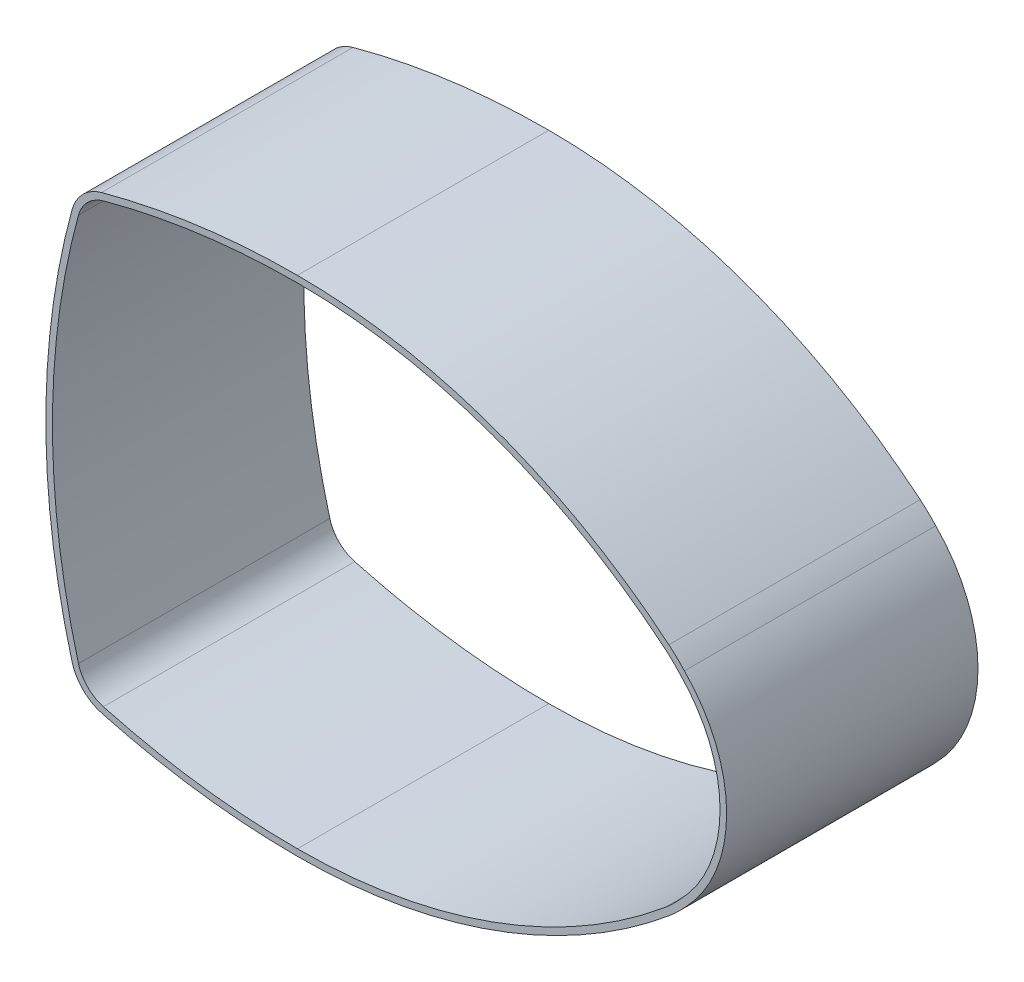
SolidWorks part; units mm, degrees
ref_plane "Спереди" through (0, 0, 0) normal (0, 0, 1) x (1, 0, 0)
ref_plane "Сверху" through (0, 0, 0) normal (0, 1, 0) x (1, 0, 0)
ref_plane "Справа" through (0, 0, 0) normal (1, 0, 0) x (0, 0, -1)
other "Configuration Table"
sketch "Эскиз1" plane through (0, 0, 0) normal (0, 0, 1) x (1, 0, 0)
  arc A87 (57.3134, 77.2573) -> (57.3134, 47.5637) centre (42.3953, 62.4105) cw
  arc A88 (58.0391, 77.9457) -> (55.6839, 80.2032) centre (40.8888, 62.4105) ccw
  arc A89 (55.6839, 80.2032) -> (-0.6112, 100.5509) centre (-0.6112, 12.5022) ccw
  arc A90 (-0.6112, 100.5509) -> (-30.2928, 96.5756) centre (-0.6112, -12.2478) ccw
  arc A91 (-30.2928, 96.5756) -> (-34.7764, 92.092) centre (-28.6112, 90.4105) ccw
  arc A92 (-34.7764, 92.092) -> (-34.7764, 32.729) centre (74.0471, 62.4105) ccw
  arc A93 (-34.7764, 32.729) -> (-30.2928, 28.2454) centre (-28.6112, 34.4105) ccw
  arc A94 (-30.2928, 28.2454) -> (-0.6112, 24.2702) centre (-0.6112, 137.0688) ccw
  arc A95 (-0.6112, 24.2702) -> (55.6839, 44.6178) centre (-0.6112, 112.3188) ccw
  arc A96 (57.3134, 77.2573) -> (55.0445, 79.4343) centre (40.8888, 62.4105) ccw
  arc A97 (55.0445, 79.4343) -> (-0.6112, 99.5509) centre (-0.6112, 12.5022) ccw
  arc A98 (55.0445, 45.3867) -> (57.3134, 47.5637) centre (40.8888, 62.4105) ccw
  arc A99 (-0.6112, 25.2702) -> (55.0445, 45.3867) centre (-0.6112, 112.3188) ccw
  arc A100 (-30.0296, 29.2101) -> (-0.6112, 25.2702) centre (-0.6112, 137.0688) ccw
  arc A101 (-33.8116, 32.9921) -> (-30.0296, 29.2101) centre (-28.6112, 34.4105) ccw
  arc A102 (-0.6112, 99.5509) -> (-30.0296, 95.6109) centre (-0.6112, -12.2478) ccw
  arc A103 (-30.0296, 95.6109) -> (-33.8116, 91.8289) centre (-28.6112, 90.4105) ccw
  arc A104 (-33.8116, 91.8289) -> (-33.8116, 32.9921) centre (74.0471, 62.4105) ccw
  arc A105 (57.3134, 77.2573) -> (55.0445, 79.4343) centre (40.8888, 62.4105) ccw
  arc A106 (55.0445, 79.4343) -> (-0.6112, 99.5509) centre (-0.6112, 12.5022) ccw
  arc A107 (55.0445, 45.3867) -> (57.3134, 47.5637) centre (40.8888, 62.4105) ccw
  arc A108 (-0.6112, 25.2702) -> (55.0445, 45.3867) centre (-0.6112, 112.3188) ccw
  arc A109 (-30.0296, 29.2101) -> (-0.6112, 25.2702) centre (-0.6112, 137.0688) ccw
  arc A110 (-33.8116, 32.9921) -> (-30.0296, 29.2101) centre (-28.6112, 34.4105) ccw
  arc A111 (-0.6112, 99.5509) -> (-30.0296, 95.6109) centre (-0.6112, -12.2478) ccw
  arc A112 (-30.0296, 95.6109) -> (-33.8116, 91.8289) centre (-28.6112, 90.4105) ccw
  arc A113 (-33.8116, 91.8289) -> (-33.8116, 32.9921) centre (74.0471, 62.4105) ccw
  arc A114 (55.6839, 44.6178) -> (58.0391, 46.8754) centre (40.8888, 62.4105) ccw
  arc A115 (58.0391, 77.9457) -> (58.0391, 46.8754) centre (42.3953, 62.4105) cw
  dimension "D2" = 1
  dimension "D1" = 2
extrude "Бобышка-Вытянуть1" add sketch "Эскиз1" along normal blind 38.1
